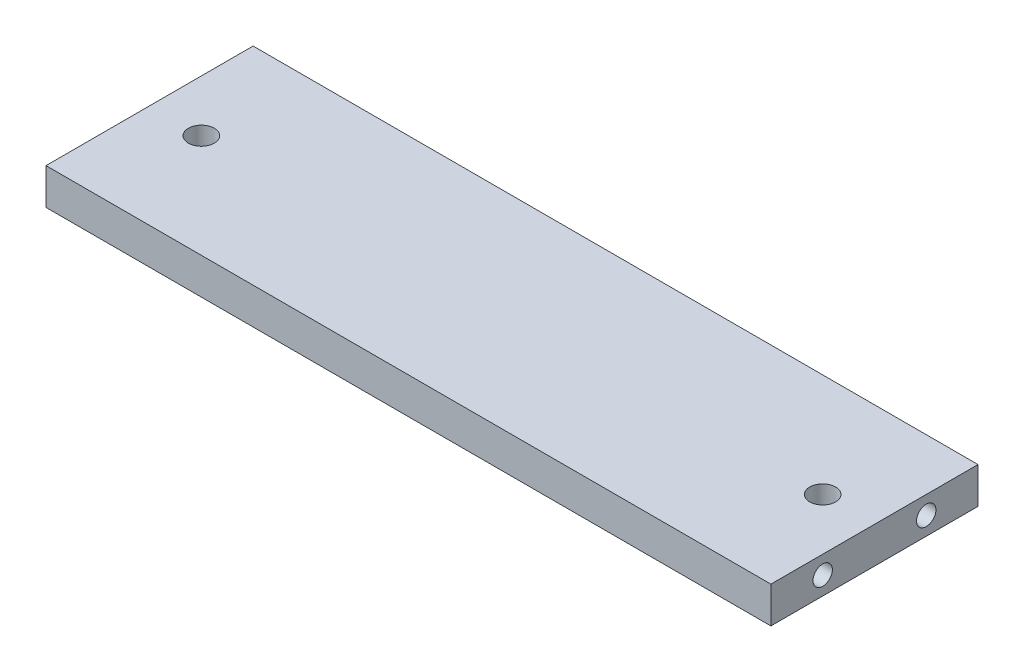
SolidWorks part; units mm, degrees
ref_plane "Front Plane" through (0, 0, 0) normal (0, 0, 1) x (1, 0, 0)
ref_plane "Top Plane" through (0, 0, 0) normal (0, 1, 0) x (1, 0, 0)
ref_plane "Right Plane" through (0, 0, 0) normal (1, 0, 0) x (0, 0, -1)
sketch "Sketch1" plane through (0, 0, 0) normal (0, 1, 0) x (1, 0, 0)
  line L0 (0, 12.7) -> (88.9, 12.7) construction
  line L1 (0, 0) -> (88.9, 0)
  line L2 (0, 0) -> (0, 25.4)
  line L3 (0, 25.4) -> (88.9, 25.4)
  line L4 (88.9, 0) -> (88.9, 25.4)
  line L5 (44.45, 25.4) -> (44.45, 0) construction
  dimension "D1" = 88.9
  dimension "D2" = 25.4
extrude "Boss-Extrude1" add sketch "Sketch1" along normal blind 4.445
sketch "Sketch3" plane through (88.9, 0, 0) normal (1, 0, 0) x (0, 0, -1)
  line L0 (0, 2.2225) -> (25.4, 2.2225) construction
  line L1 (0, 4.445) -> (0, 0) construction
  line L2 (25.4, 4.445) -> (25.4, 0) construction
  line L3 (12.7, 4.445) -> (12.7, 0) construction
  line L4 (0, 4.445) -> (25.4, 4.445) construction
  line L5 (0, 0) -> (25.4, 0) construction
  circle A0 centre (19.05, 2.2225) radius 1.1906
  circle A1 centre (6.35, 2.2225) radius 1.1906
  dimension "D1" = 2.3813
  dimension "D2" = 6.35
extrude "Cut-Extrude2" cut sketch "Sketch3" against normal blind 9.525
sketch "Sketch4" plane through (0, 4.445, 0) normal (0, 1, 0) x (1, 0, 0)
  line L0 (0, 12.7) -> (88.9, 12.7) construction
  line L1 (0, 25.4) -> (0, 0) construction
  line L2 (88.9, 0) -> (88.9, 25.4) construction
  circle A0 centre (6.35, 12.7) radius 1.5875
  circle A1 centre (82.55, 12.7) radius 1.5875
  dimension "D1" = 3.175
  dimension "D2" = 6.35
  dimension "D3" = 6.35
extrude "Cut-Extrude3" cut sketch "Sketch4" against normal through all
